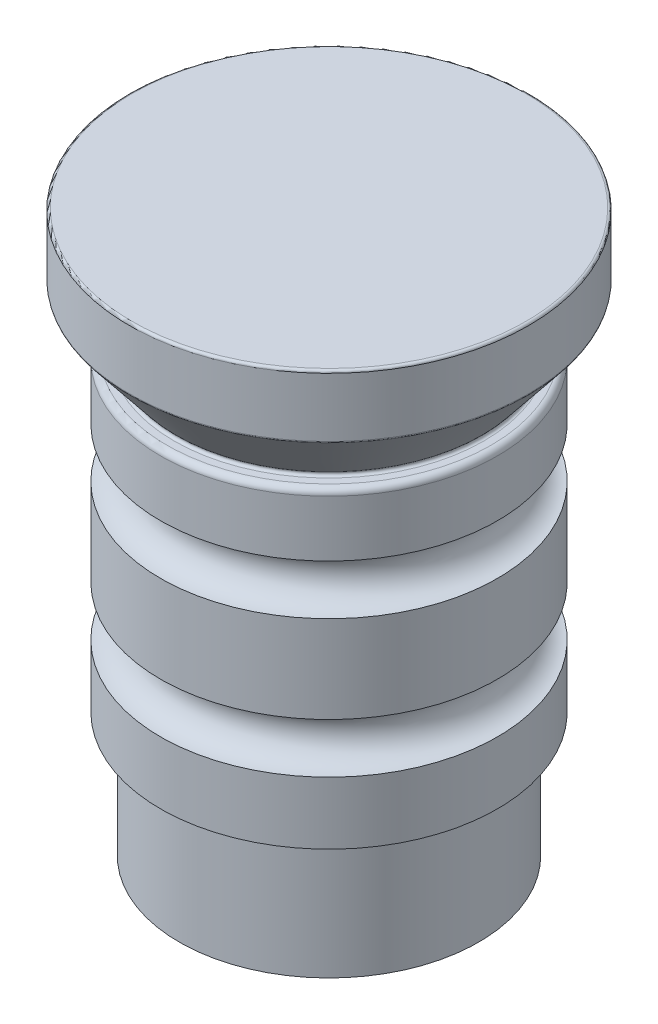
SolidWorks part; units mm, degrees
ref_plane "Plan de face" through (0, 0, 0) normal (0, 0, 1) x (1, 0, 0)
ref_plane "Plan de dessus" through (0, 0, 0) normal (0, 1, 0) x (1, 0, 0)
ref_plane "Plan de droite" through (0, 0, 0) normal (1, 0, 0) x (0, 0, -1)
sketch "Esquisse1" plane through (0, 0, 0) normal (0, 0, 1) x (1, 0, 0)
  line L1 (0, 4) -> (-7.5, 4)
  line L2 (-7.5, 4) -> (-7.5, 5)
  line L3 (-7.5, 5) -> (-10, 5)
  line L4 (-10, 5) -> (-10, 0)
  line L5 (-10, 0) -> (-12, 0)
  line L6 (-12, 0) -> (-12, 10)
  line L7 (-12, 10) -> (-13.5, 10)
  line L8 (-13.5, 10) -> (-13.5, 15)
  line L9 (-13.5, 19) -> (-13.5, 26)
  line L10 (-13.5, 30) -> (-13.5, 35)
  line L11 (-13.5, 35) -> (0, 35) construction
  line L12 (0, 35) -> (0, 4)
  line L18 (0, 40) -> (0, 35)
  line L19 (-16, 40) -> (-16, 45)
  line L20 (-16, 45) -> (0, 45)
  line L21 (0, 45) -> (0, 40)
  line L22 (-16, 40) -> (0, 40) construction
  line L23 (-13.5, 35) -> (-12, 35)
  line L24 (-12, 35) -> (-16, 40)
  arc A0 (-13.5, 30) -> (-13.5, 26) centre (-13.5, 28) cw
  arc A1 (-13.5, 19) -> (-13.5, 15) centre (-13.5, 17) cw
  point P23 (-12.75, 10)
  dimension "D1" = 2
  dimension "D2" = 7
  dimension "D3" = 5
  dimension "D4" = 5
  dimension "D5" = 12
  dimension "D6" = 13.5
  dimension "D7" = 1
  dimension "D8" = 2.5
  dimension "D9" = 7.5
  dimension "D10" = 5
  dimension "D11" = 5
  dimension "D12" = 1.5
  dimension "D13" = 5
  dimension "D14" = 5
  dimension "D15" = 16
revolve "Révolution1" add sketch "Esquisse1" angle 360 about L12
fillet "Congé2" radius 0.5 1 edges at (-13.5, 35, 0)
fillet "Congé3" radius 0.2 5 edges at (-16, 45, 0) (-16, 40, 0) (-7.5, 4, 0) (-10, 5, 0) (-12, 35, 0)
